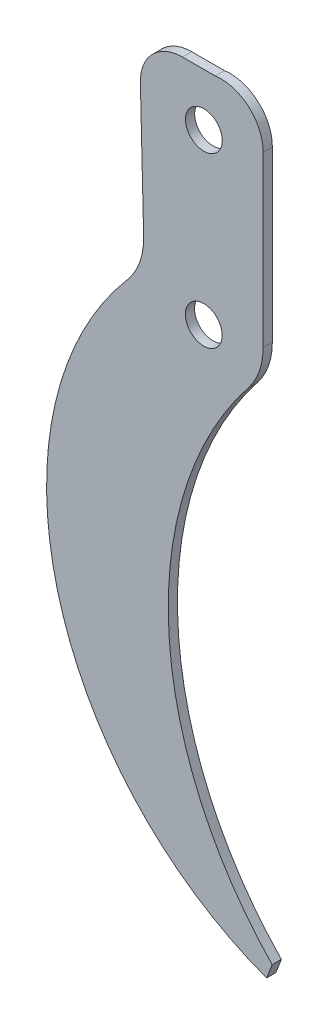
SolidWorks part; units mm, degrees
material "AISI 1020"
ref_plane "Ön Düzlem" through (0, 0, 0) normal (0, 0, 1) x (1, 0, 0)
ref_plane "Üst Düzlem" through (0, 0, 0) normal (0, 1, 0) x (1, 0, 0)
ref_plane "Sağ Düzlem" through (0, 0, 0) normal (1, 0, 0) x (0, 0, -1)
sketch "Model" plane through (0, 0, 0) normal (0, 0, 1) x (1, 0, 0)
  line L16 (6931.1943, 3942.0861) -> (6931.1943, 3666.3646)
  line L17 (6799.8465, 4010.7595) -> (6853.0522, 4010.7595)
  line L18 (6736.5354, 3726.0968) -> (6731.1943, 3940.3749)
  line L19 (6945.9409, 2803.0728) -> (6936.879, 2779.773)
  arc A0 (6710.2051, 3651.9541) -> (6736.5354, 3726.0968) centre (6626.692, 3723.3589) ccw
  arc A1 (6799.8465, 4010.7595) -> (6731.1943, 3940.3749) centre (6799.8465, 3942.0861) ccw
  arc A2 (6931.1943, 3942.0861) -> (6853.0522, 4010.7595) centre (6862.524, 3942.7424) ccw
  circle A3 centre (6834.6326, 3925.2186) radius 40
  circle A4 centre (6834.4692, 3650.2186) radius 40
  arc A5 (6907.3191, 3597.9784) -> (6931.1943, 3666.3646) centre (6821.3168, 3666.3646) ccw
  arc A6 (6710.2051, 3651.9541) -> (6936.879, 2779.773) centre (7127.7705, 3294.9305) ccw
  arc A7 (6907.3191, 3597.9784) -> (6945.9409, 2803.0728) centre (7380.9224, 3222.5981) ccw
  dimension "D2" = 80
  dimension "D3" = 80
  dimension "D5" = 200
  dimension "D1" = 1150
  dimension "D4" = 275
  dimension "D6" = 25
extrude "Yükseklik-Ekstrüzyon1" add sketch "Model" along normal blind 15
sketch "Çizim1" plane through (0, 0, 15) normal (0, 0, 1) x (1, 0, 0)
  circle A0 centre (6834.4692, 3650.2186) radius 40 construction
  circle A1 centre (6834.6326, 3925.2186) radius 40 construction
  circle A2 centre (6834.4692, 3650.2186) radius 40
  circle A3 centre (6834.6326, 3925.2186) radius 40
  circle A4 centre (6834.6326, 3925.2186) radius 30
  circle A5 centre (6834.4692, 3650.2186) radius 30
  dimension "D1" = 60
  dimension "D2" = 60
extrude "Yükseklik-Ekstrüzyon3" add sketch "Çizim1" against normal up to surface (15 mm away) up to face at (6812.0105, 3609.0752, 0)
